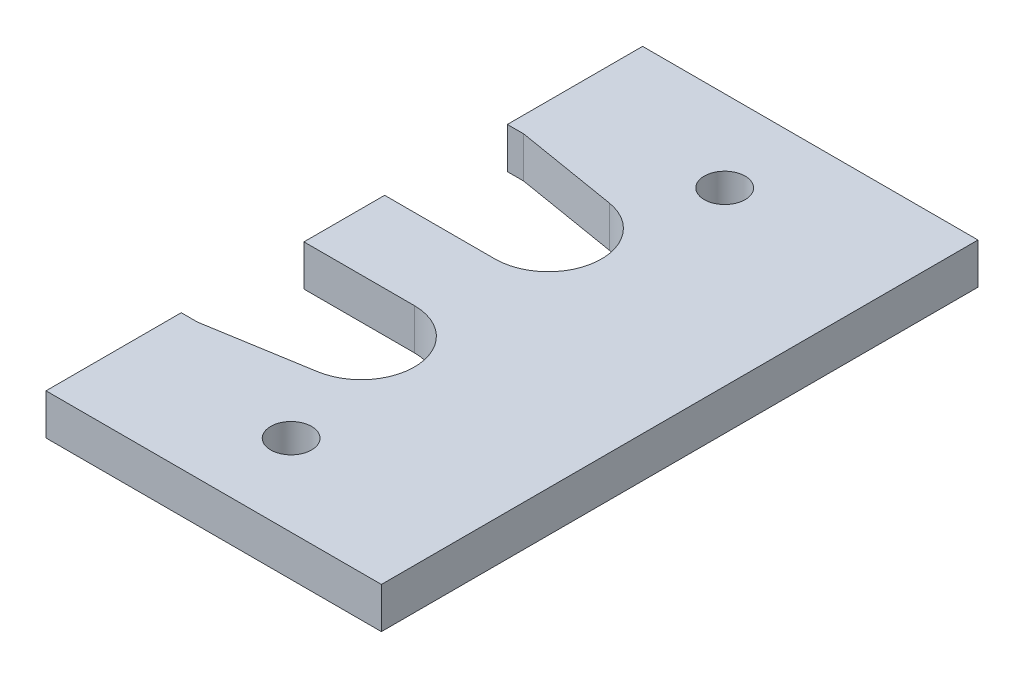
SolidWorks part; units mm, degrees
ref_plane "Front Plane" through (0, 0, 0) normal (0, 0, 1) x (1, 0, 0)
ref_plane "Top Plane" through (0, 0, 0) normal (0, 1, 0) x (1, 0, 0)
ref_plane "Right Plane" through (0, 0, 0) normal (1, 0, 0) x (0, 0, -1)
sketch "Sketch2" plane through (0, 0, 0) normal (0, 1, 0) x (1, 0, 0)
  line L0 (-5.2988, -43.9481) -> (35.7012, -43.9481)
  line L1 (-5.2988, 28.9831) -> (35.7012, 28.9831)
  line L3 (-5.2988, -2.5513) -> (-5.2988, -12.4137)
  line L4 (35.7012, 28.9831) -> (35.7012, -43.9481)
  line L5 (-5.2988, -27.4137) -> (-3.2988, -27.4137)
  line L6 (0.5147, -7.4825) -> (21.224, -7.4825) construction
  line L8 (-5.2988, 12.4487) -> (-5.2988, 28.9831)
  line L9 (-3.2988, -27.4137) -> (9.2667, -25.3258)
  line L10 (8.2012, -12.4137) -> (-5.2988, -12.4137)
  line L11 (-5.2988, -27.4137) -> (-5.2988, -43.9481)
  line L18 (8.2012, -2.5513) -> (-5.2988, -2.5513)
  line L19 (-3.2988, 12.4487) -> (9.2667, 10.3608)
  line L20 (-5.2988, 12.4487) -> (-3.2988, 12.4487)
  arc A1 (8.2012, -12.4137) -> (9.2667, -25.3258) centre (8.2012, -18.9137) cw
  circle A2 centre (14.7012, -33.9825) radius 2.5
  circle A3 centre (14.7012, 19.0175) radius 2.5
  arc A5 (8.2012, -2.5513) -> (9.2667, 10.3608) centre (8.2012, 3.9487) ccw
  point P0 (-5.2988, -7.4825)
  point P19 (35.7012, -7.4825)
  point P23 (35.7012, -7.4825)
  point P24 (-5.2988, -7.4825)
  dimension "D1" = 5
  dimension "D2" = 26.5
extrude "Boss-Extrude1" add sketch "Sketch2" along normal blind 5
